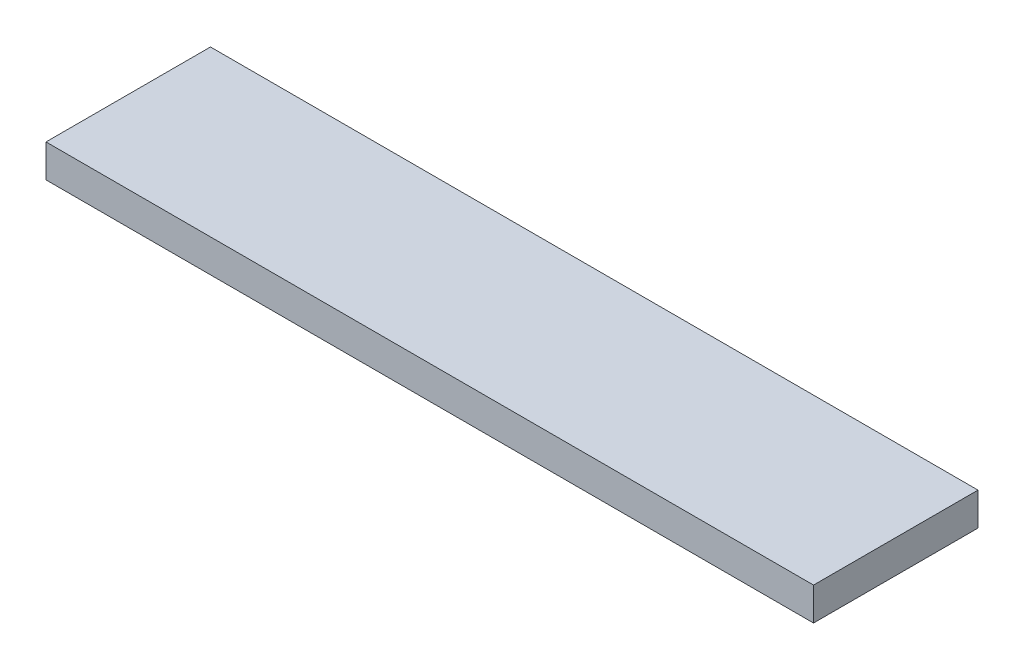
SolidWorks part; units mm, degrees
ref_plane "Front Plane" through (0, 0, 0) normal (0, 0, 1) x (1, 0, 0)
ref_plane "Top Plane" through (0, 0, 0) normal (0, 1, 0) x (1, 0, 0)
ref_plane "Right Plane" through (0, 0, 0) normal (1, 0, 0) x (0, 0, -1)
sketch "Sketch1" plane through (0, 0, 0) normal (0, 1, 0) x (1, 0, 0)
  line L1 (-175, 37.5) -> (175, 37.5)
  line L2 (-175, 37.5) -> (-175, -37.5)
  line L3 (-175, -37.5) -> (175, -37.5)
  line L4 (175, 37.5) -> (175, -37.5)
  line L5 (-175, 37.5) -> (175, -37.5) construction
  line L6 (-175, -37.5) -> (175, 37.5) construction
  point P0 (0, 0)
extrude "Boss-Extrude1" add sketch "Sketch1" along normal blind 15
